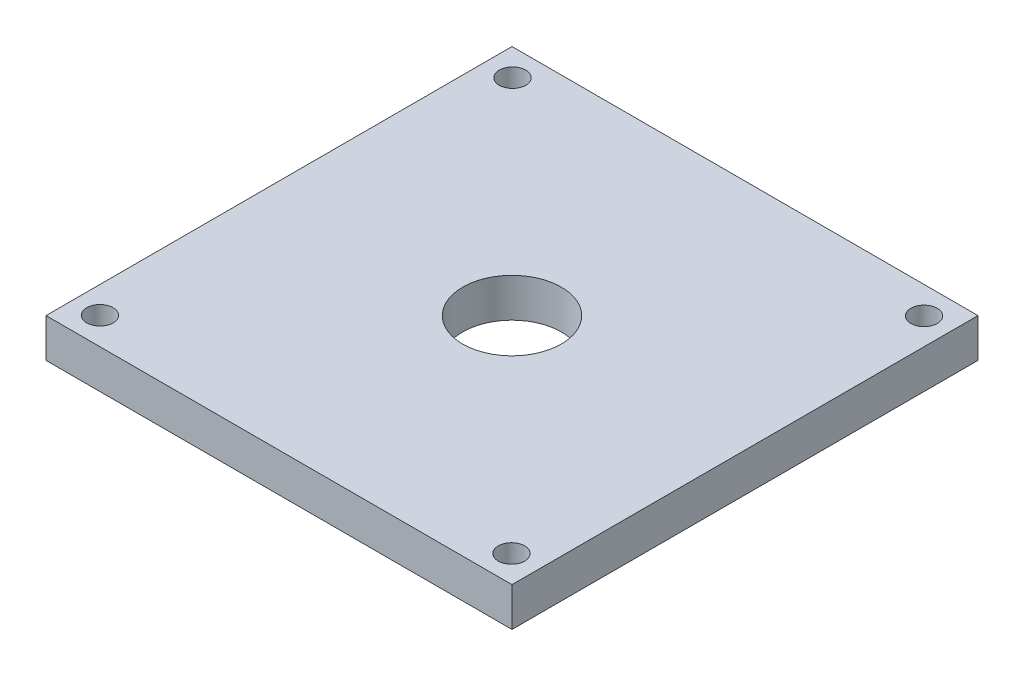
SolidWorks part; units mm, degrees
ref_plane "前视基准面" through (0, 0, 0) normal (0, 0, 1) x (1, 0, 0)
ref_plane "上视基准面" through (0, 0, 0) normal (0, 1, 0) x (1, 0, 0)
ref_plane "右视基准面" through (0, 0, 0) normal (1, 0, 0) x (0, 0, -1)
other "Configuration Table"
sketch "草图3" plane through (0, 0, 0) normal (0, 1, 0) x (1, 0, 0)
  line L0 (30, 60) -> (30, 30) construction
  line L1 (0, 0) -> (60, 0)
  line L2 (0, 0) -> (0, 60)
  line L3 (0, 60) -> (60, 60)
  line L4 (60, 0) -> (60, 60)
  circle A2 centre (3.5053, 56.5602) radius 1.7
  circle A3 centre (56.5602, 56.4947) radius 1.7
  circle A4 centre (56.4947, 3.4398) radius 1.7
  circle A5 centre (3.4398, 3.5053) radius 1.7
  circle A6 centre (30, 30) radius 6.35
  point P22 (30, 30)
  dimension "D5" = 12.7
  dimension "D7" = 3.4
  dimension "D1" = 60
  dimension "D2" = 60
  dimension "D3" = 30
  dimension "D4" = 30
  dimension "D8" = 4
extrude "凸台-拉伸1" add sketch "草图3" along normal blind 5
